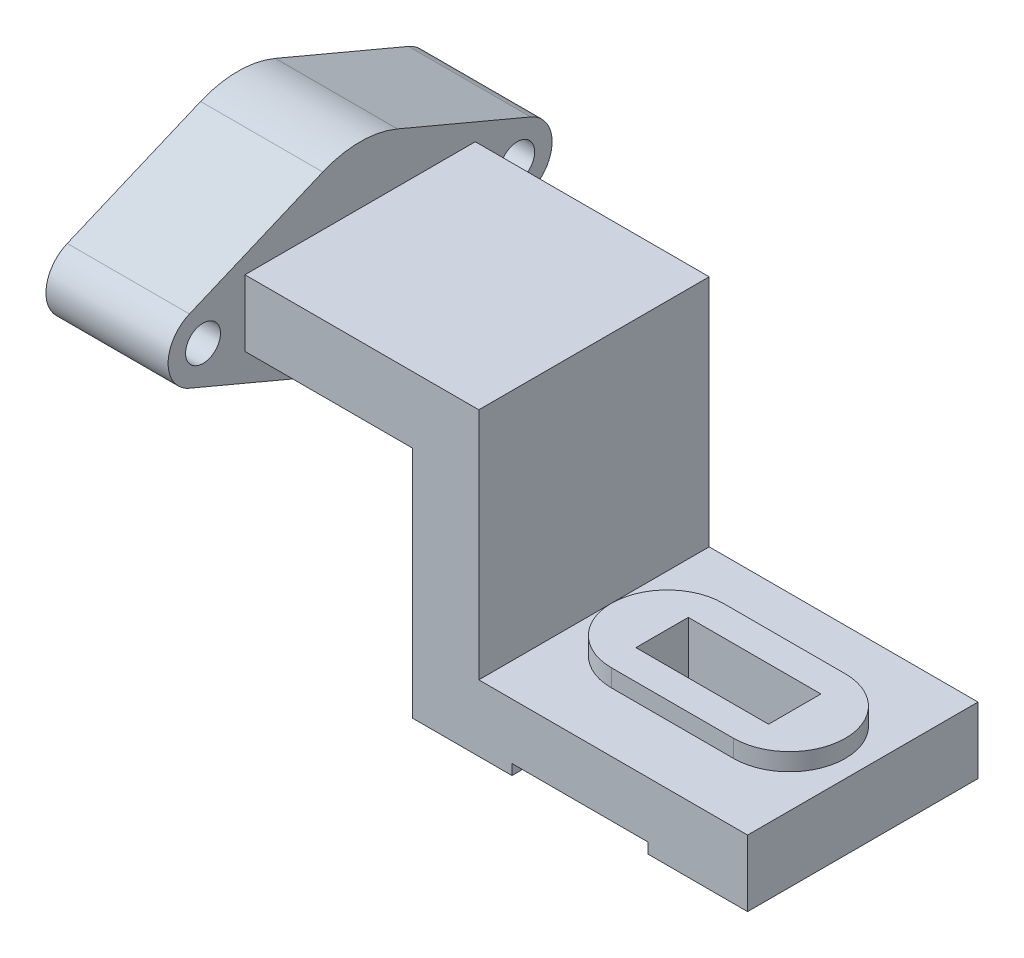
SolidWorks part; units mm, degrees
ref_plane "Front Plane" through (0, 0, 0) normal (0, 0, 1) x (1, 0, 0)
ref_plane "Top Plane" through (0, 0, 0) normal (0, 1, 0) x (1, 0, 0)
ref_plane "Right Plane" through (0, 0, 0) normal (1, 0, 0) x (0, 0, -1)
sketch "Sketch1" plane through (0, 0, 0) normal (0, 0, 1) x (1, 0, 0)
  line L0 (-96, 86) -> (-29, 86)
  line L1 (-29, 86) -> (-29, 19)
  line L2 (-29, 19) -> (48, 19)
  line L3 (48, 19) -> (48, 0)
  line L4 (48, 0) -> (19.5, 0)
  line L5 (-48, 0) -> (-48, 67)
  line L6 (-48, 67) -> (-96, 67)
  line L7 (-96, 67) -> (-96, 86)
  line L8 (-19.5, 0) -> (-19.5, 3)
  line L9 (-19.5, 3) -> (19.5, 3)
  line L10 (19.5, 3) -> (19.5, 0)
  line L11 (0, 0) -> (0, 17.7925) construction
  line L12 (-19.5, 0) -> (-48, 0)
  point P15 (-154.1233, 52.6108)
  dimension "D1" = 3
  dimension "D2" = 86
  dimension "D3" = 144
  dimension "D4" = 19
  dimension "D5" = 19
  dimension "D6" = 19
  dimension "D7" = 39
  dimension "D8" = 96
extrude "Boss-Extrude1" add sketch "Sketch1" along normal mid plane 66
sketch "Sketch2" plane through (0, 19, 0) normal (0, 1, 0) x (1, 0, 0)
  line L0 (9.5, 33) -> (9.5, -53.4306) construction
  line L1 (48, 33) -> (-29, 33) construction
  line L2 (48, 0) -> (-13.7413, 0) construction
  line L3 (48, -33) -> (48, 33) construction
  line L4 (-8, 0) -> (27, 0) construction
  line L5 (-8, 16) -> (27, 16)
  line L6 (-8, -16) -> (27, -16)
  arc A0 (-8, 16) -> (-8, -16) centre (-8, 0) ccw
  arc A1 (27, -16) -> (27, 16) centre (27, 0) ccw
  point P11 (9.5, 0)
  dimension "D2" = 16
  dimension "D1" = 35
extrude "Boss-Extrude2" add sketch "Sketch2" along normal blind 5
sketch "Sketch3" plane through (0, 24, 0) normal (0, 1, 0) x (1, 0, 0)
  line L0 (48, 0) -> (-32.1214, 0) construction
  line L1 (48, -33) -> (48, 33) construction
  line L2 (9.5, 33) -> (9.5, -41.3196) construction
  line L3 (48, 33) -> (-29, 33) construction
  line L5 (-9.5, 7.5) -> (28.5, 7.5)
  line L6 (-9.5, 7.5) -> (-9.5, -7.5)
  line L7 (-9.5, -7.5) -> (28.5, -7.5)
  line L8 (28.5, 7.5) -> (28.5, -7.5)
  line L9 (-9.5, 7.5) -> (28.5, -7.5) construction
  line L10 (-9.5, -7.5) -> (28.5, 7.5) construction
  point P9 (9.5, 0)
  point P14 (9.5, 0)
  dimension "D1" = 38
  dimension "D2" = 15
extrude "Cut-Extrude1" cut sketch "Sketch3" against normal through all
sketch "Sketch4" plane through (-96, 0, 0) normal (-1, 0, 0) x (0, 0, 1)
  line L0 (0, -47.3) -> (0, 47.3) construction
  line L1 (33, 0) -> (-33, 0) construction
  line L2 (-48.8889, 84.2128) -> (-10.6944, 100.3353)
  line L3 (0, 75) -> (111.8233, 75) construction
  line L4 (0, 75) -> (0, 158.8191) construction
  line L5 (48.8889, 84.2128) -> (10.6944, 100.3353)
  line L6 (48.8889, 65.7872) -> (10.6944, 49.6647)
  line L7 (-48.8889, 65.7872) -> (-10.6944, 49.6647)
  arc A0 (-10.6944, 49.6647) -> (10.6944, 49.6647) centre (0, 75) ccw
  arc A1 (48.8889, 65.7872) -> (48.8889, 84.2128) centre (45, 75) ccw
  arc A2 (-48.8889, 65.7872) -> (-48.8889, 84.2128) centre (-45, 75) cw
  arc A3 (10.6944, 100.3353) -> (-10.6944, 100.3353) centre (0, 75) ccw
  circle A4 centre (-45, 75) radius 5
  circle A5 centre (45, 75) radius 5
  dimension "D1" = 55
  dimension "D2" = 20
  dimension "D5" = 10
  dimension "D3" = 90
  dimension "D4" = 75
extrude "Boss-Extrude3" add sketch "Sketch4" along normal blind 35
hole_wizard "Hole1" positions "Sketch5" profile "Sketch6" legacy
sketch "Sketch5" plane through (-131, 0, 0) normal (-1, 0, 0) x (0, 0, 1)
  point P0 (0, 75)
sketch "Sketch6" plane through (-131, 75, 0) normal (0, 1, 0) x (0, 0, 1)
  line L0 (0, 0) -> (0, 34)
  line L1 (0, 34) -> (17.5, 34)
  line L2 (17.5, 34) -> (17.5, 0)
  line L3 (17.5, 0) -> (0, 0)
  line L4 (0, 110) -> (0, -10) construction
  dimension "Diameter" = 35
  dimension "Depth" = 34
